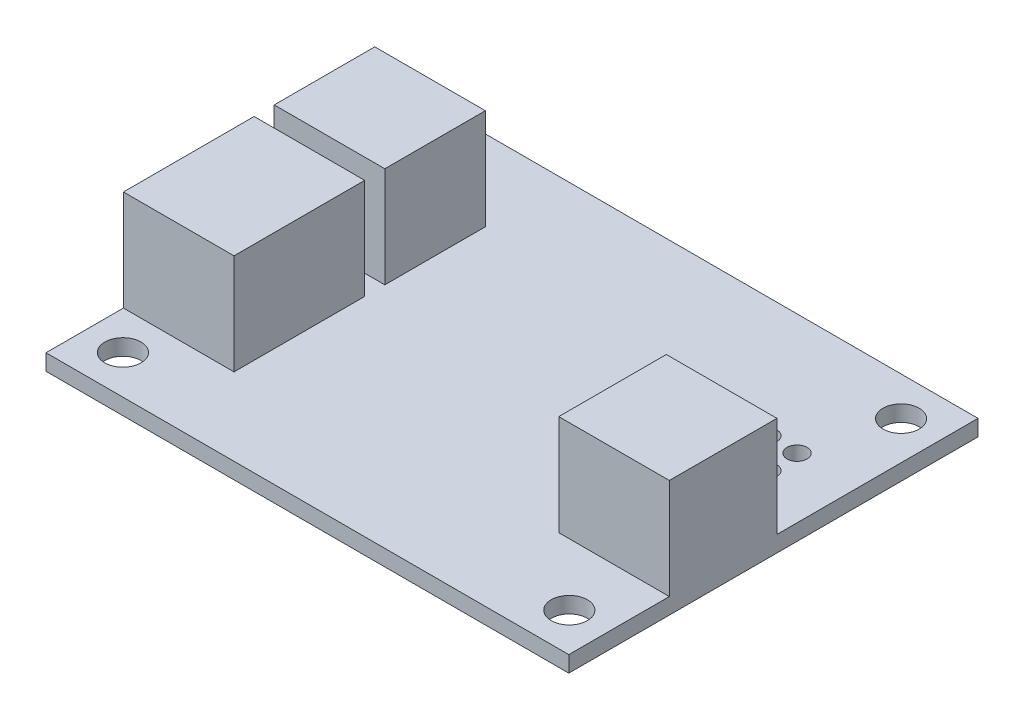
SolidWorks part; units mm, degrees
ref_plane "Front Plane" through (0, 0, 0) normal (0, 0, 1) x (1, 0, 0)
ref_plane "Top Plane" through (0, 0, 0) normal (0, 1, 0) x (1, 0, 0)
ref_plane "Right Plane" through (0, 0, 0) normal (1, 0, 0) x (0, 0, -1)
sketch "Sketch1" plane through (0, 0, 0) normal (0, 1, 0) x (1, 0, 0)
  line L0 (26, 36.85) -> (26, 40.7) construction
  line L1 (0, 0) -> (52, 0)
  line L2 (0, 0) -> (0, 40.7)
  line L3 (0, 40.7) -> (52, 40.7)
  line L4 (52, 0) -> (52, 40.7)
  line L5 (3.8, 36.85) -> (48.2, 36.85) construction
  line L6 (3.8, 36.85) -> (3.8, 3.85) construction
  line L7 (3.8, 3.85) -> (48.2, 3.85) construction
  line L8 (48.2, 36.85) -> (48.2, 3.85) construction
  line L9 (48.2, 20.35) -> (52, 20.35) construction
  circle A0 centre (3.8, 36.85) radius 1.8
  circle A1 centre (48.2, 36.85) radius 1.8
  circle A2 centre (48.2, 3.85) radius 1.8
  circle A3 centre (3.8, 3.85) radius 1.8
  dimension "D5" = 3.6
  dimension "D1" = 40.7
  dimension "D2" = 52
  dimension "D3" = 44.4
  dimension "D4" = 33
extrude "Boss-Extrude1" add sketch "Sketch1" along normal blind 1.6
sketch "Sketch2" plane through (0, 1.6, 0) normal (0, 1, 0) x (1, 0, 0)
  line L0 (52, 0) -> (52, 40.7) construction
  line L1 (52, 10) -> (41, 10)
  line L2 (52, 10) -> (52, 20.7)
  line L3 (52, 20.7) -> (41, 20.7)
  line L4 (41, 10) -> (41, 20.7)
  line L5 (0, 40.7) -> (0, 0) construction
  line L6 (0, 32.7) -> (11, 32.7)
  line L7 (0, 32.7) -> (0, 22.7)
  line L8 (0, 22.7) -> (11, 22.7)
  line L9 (11, 32.7) -> (11, 22.7)
  line L10 (0, 0) -> (52, 0) construction
  line L11 (0, 20.7) -> (11, 20.7)
  line L12 (0, 20.7) -> (0, 7.7)
  line L13 (0, 7.7) -> (11, 7.7)
  line L14 (11, 20.7) -> (11, 7.7)
  line L15 (52, 40.7) -> (0, 40.7) construction
  dimension "D1" = 11
  dimension "D2" = 10
  dimension "D3" = 20
  dimension "D4" = 8
  dimension "D5" = 18
  dimension "D6" = 20
  dimension "D7" = 33
extrude "Boss-Extrude2" add sketch "Sketch2" along normal blind 10
sketch "Sketch3" plane through (0, 1.6, 0) normal (0, 1, 0) x (1, 0, 0)
  line L0 (52, 40.7) -> (0, 40.7) construction
  line L1 (52, 20.7) -> (52, 40.7) construction
  circle A0 centre (46, 25.7) radius 1
  circle A1 centre (43, 25.7) radius 1
  circle A2 centre (40, 25.7) radius 1
  circle A3 centre (43, 28.7) radius 1
  circle A4 centre (40, 28.7) radius 1
  circle A5 centre (46, 28.7) radius 1
  dimension "D1" = 2
  dimension "D4" = 12
  dimension "D5" = 6
  dimension "D2" = 3
  dimension "D3" = 2
extrude "Cut-Extrude1" cut sketch "Sketch3" against normal through all
